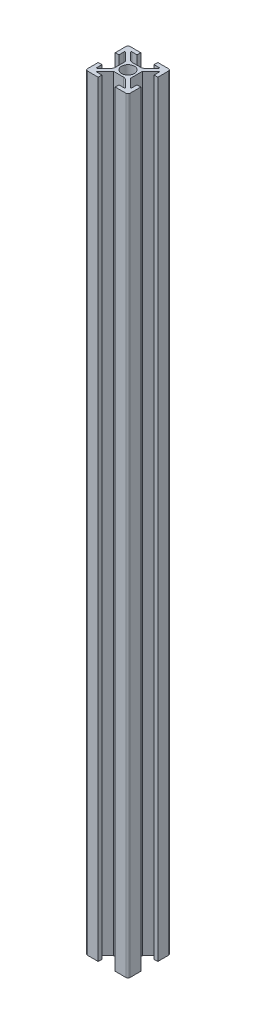
SolidWorks part; units mm, degrees
material "6063-T5"
ref_plane "Plano frontal" through (0, 0, 0) normal (0, 0, 1) x (1, 0, 0)
ref_plane "Plano superior" through (0, 0, 0) normal (0, 1, 0) x (1, 0, 0)
ref_plane "Plano direito" through (0, 0, 0) normal (1, 0, 0) x (0, 0, -1)
sketch "Esboço1" plane through (0, 0, 0) normal (0, 1, 0) x (1, 0, 0)
  line L1 (-10, 10) -> (10, 10)
  line L2 (-10, 10) -> (-10, -10)
  line L3 (-10, -10) -> (10, -10)
  line L4 (10, 10) -> (10, -10)
  line L5 (-10, 10) -> (10, -10) construction
  line L6 (-10, -10) -> (10, 10) construction
  circle A0 centre (0, 0) radius 3
  dimension "D1" = 6
  dimension "D2" = 20
  dimension "D3" = 20
extrude "Ressalto-extrusão1" add sketch "Esboço1" along normal mid plane 360
sketch "Esboço2" plane through (0, 180, 0) normal (0, 1, 0) x (1, 0, 0)
  line L0 (10, 10) -> (-10, 10) construction
  line L1 (-4, 4) -> (4, 4)
  line L2 (-4, 4) -> (-4, -4)
  line L3 (-4, -4) -> (4, -4)
  line L4 (4, 4) -> (4, -4)
  line L5 (-4, 4) -> (4, -4) construction
  line L6 (-4, -4) -> (4, 4) construction
  line L7 (0, 10) -> (0, -10) construction
  line L8 (-10, -10) -> (10, -10) construction
  line L9 (-4, 10) -> (4, 10)
  line L10 (-4, 10) -> (-4, 8.25)
  line L11 (4, 10) -> (4, 8.25)
  line L12 (-4, 8.25) -> (4, 8.25)
  line L13 (-7.05, 8.25) -> (7.05, 8.25)
  line L14 (-7.05, 8.25) -> (-2.8, 4)
  line L15 (7.05, 8.25) -> (2.8, 4)
  line L16 (2.8, 4) -> (-2.8, 4)
  point P0 (0, 0)
  point P19 (0, 8.25)
  line M7 (10, 10) -> (-10, 10)
  dimension "D1" = 8
  dimension "D2" = 8
  dimension "D3" = 1.75
  dimension "D4" = 8
  dimension "D5" = 14.1
  dimension "D6" = 45
  dimension "D7" = 45
extrude "Corte-extrusão1" cut sketch "Esboço2" against normal through all contours L15 L13 L12 L14 L1 | L10 L12 L11 M7
pattern_circular "PadrãoCircular2" count 4 over 360 about axis through (0, 0, 0) along (0, 1, 0) of "Corte-extrusão1"
fillet "Filete2" radius 1 4 edges at (10, 0, 10) (-10, 0, 10) (-10, 0, -10) (10, 0, -10)
fillet "Filete3" radius 2 4 edges at (2.8, 0, 4) (-4, 0, 2.8) (2.8, 0, -4) (-2.8, 0, -4)
fillet "Filete4" radius 0.25 8 edges at (8.25, 0, 7.05) (7.05, 0, 8.25) (-8.25, 0, 7.05) (-7.05, 0, 8.25) (8.25, 0, -7.05) (7.05, 0, -8.25) (-8.25, 0, -7.05) (-7.05, 0, -8.25)
